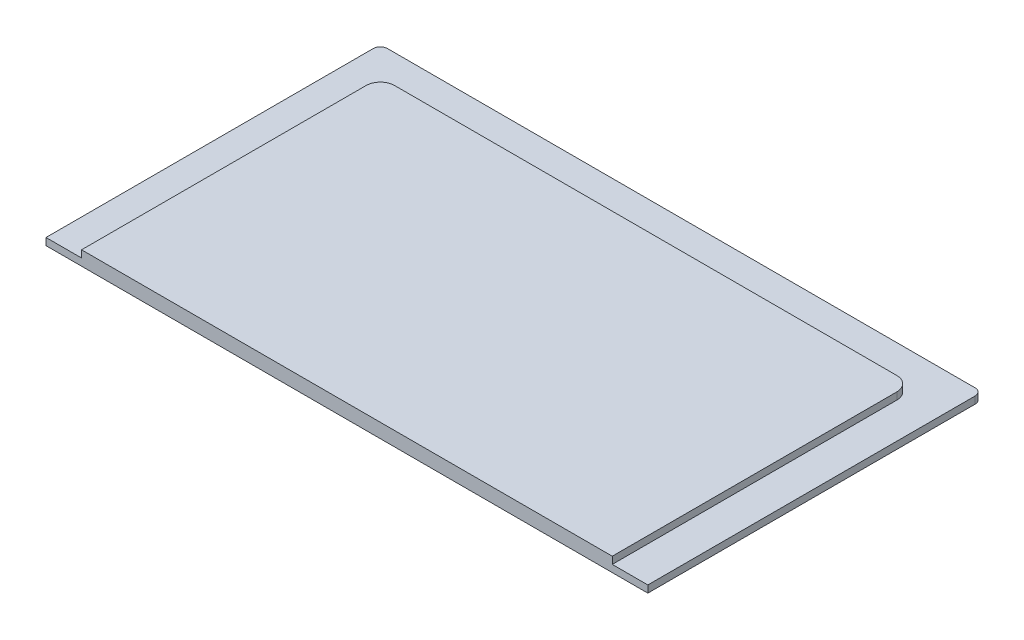
SolidWorks part; units mm, degrees
material "Стекло"
ref_plane "Спереди" through (0, 0, 0) normal (0, 0, 1) x (1, 0, 0)
ref_plane "Сверху" through (0, 0, 0) normal (0, 1, 0) x (1, 0, 0)
ref_plane "Справа" through (0, 0, 0) normal (1, 0, 0) x (0, 0, -1)
sketch "Эскиз1" plane through (0, 0, 0) normal (0, 1, 0) x (1, 0, 0)
  line L1 (-37.3, -21) -> (37.3, -21)
  line L2 (-37.3, -21) -> (-37.3, 21)
  line L3 (-37.3, 21) -> (37.3, 21)
  line L4 (37.3, -21) -> (37.3, 21)
  line L5 (-37.3, -21) -> (37.3, 21) construction
  line L6 (-37.3, 21) -> (37.3, -21) construction
  point P0 (0, 0)
  dimension "D1" = 42
  dimension "D2" = 74.6
extrude "Бобышка-Вытянуть1" add sketch "Эскиз1" along normal blind 1
fillet "Скругление1" radius 2 2 edges at (-37.3, 0.5, -21) (37.3, 0.5, -21)
sketch "Эскиз2" plane through (0, 0, 0) normal (0, -1, 0) x (1, 0, 0)
  line L0 (-37.3, 21) -> (37.3, 21) construction
  line L1 (-42.3, 21) -> (42.3, 21)
  line L2 (-42.3, 21) -> (-42.3, -26)
  line L3 (-42.3, -26) -> (42.3, -26)
  line L4 (42.3, 21) -> (42.3, -26)
  line L5 (-37.3, -19) -> (-37.3, 21) construction
  line L6 (37.3, 21) -> (37.3, -19) construction
  line L7 (35.3, -21) -> (-35.3, -21) construction
  dimension "D1" = 5
  dimension "D2" = 5
  dimension "D3" = 5
extrude "Бобышка-Вытянуть2" add sketch "Эскиз2" along normal blind 1
fillet "Скругление2" radius 1 2 edges at (42.3, -0.5, -26) (-42.3, -0.5, -26)
